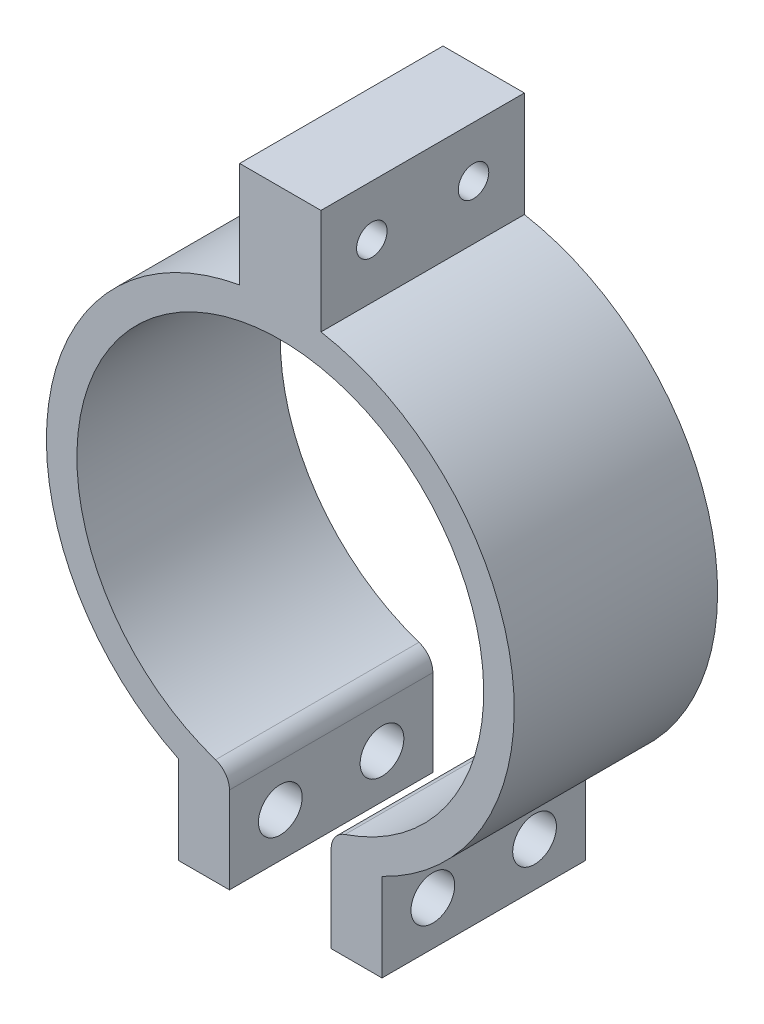
SolidWorks part; units mm, degrees
ref_plane "前视基准面" through (0, 0, 0) normal (0, 0, 1) x (1, 0, 0)
ref_plane "上视基准面" through (0, 0, 0) normal (0, 1, 0) x (1, 0, 0)
ref_plane "右视基准面" through (0, 0, 0) normal (1, 0, 0) x (0, 0, -1)
sketch "草图1" plane through (0, 0, 0) normal (0, 0, 1) x (1, 0, 0)
  circle A0 centre (0, 0) radius 20
  circle A1 centre (0, 0) radius 23
  dimension "D1" = 40
  dimension "D2" = 46
extrude "凸台-拉伸1" add sketch "草图1" along normal blind 20
sketch "草图2" plane through (0, 0, 20) normal (0, 0, 1) x (1, 0, 0)
  line L1 (5, -10.1845) -> (-5, -10.1845)
  line L2 (5, -10.1845) -> (5, -29.8155)
  line L3 (5, -29.8155) -> (-5, -29.8155)
  line L4 (-5, -10.1845) -> (-5, -29.8155)
  line L5 (5, -10.1845) -> (-5, -29.8155) construction
  line L6 (5, -29.8155) -> (-5, -10.1845) construction
  circle A0 centre (0, 0) radius 20 construction
  point P0 (0, -20)
  dimension "D1" = 10
extrude "切除-拉伸1" cut sketch "草图2" against normal blind 20
sketch "草图3" plane through (0, 0, 20) normal (0, 0, 1) x (1, 0, 0)
  line L1 (-5, -19.3649) -> (-10, -19.3649)
  line L2 (-5, -19.3649) -> (-5, -29.3649)
  line L3 (-5, -29.3649) -> (-10, -29.3649)
  line L4 (-10, -19.3649) -> (-10, -29.3649)
  line L5 (5, -19.3649) -> (10, -19.3649)
  line L6 (5, -19.3649) -> (5, -29.3649)
  line L7 (5, -29.3649) -> (10, -29.3649)
  line L8 (10, -19.3649) -> (10, -29.3649)
  dimension "D1" = 5
  dimension "D2" = 5
  dimension "D3" = 10
  dimension "D4" = 10
extrude "凸台-拉伸2" add sketch "草图3" against normal blind 20
fillet "圆角1" radius 2 2 edges at (-5, -19.3649, 10) (5, -19.3649, 10)
sketch "草图4" plane through (10, 0, 0) normal (1, 0, 0) x (0, 0, -1)
  line L0 (-20, -29.3649) -> (-20, -20.7123) construction
  line L1 (0, -29.3649) -> (0, -20.7123) construction
  line L2 (0, -29.3649) -> (-20, -29.3649) construction
  circle A0 centre (-15, -25.0386) radius 2.15
  circle A1 centre (-5, -25.0386) radius 2.15
  dimension "D1" = 4.3
  dimension "D2" = 4.3
  dimension "D3" = 5
  dimension "D4" = 5
  dimension "D5" = 4.3263
  dimension "D6" = 4.3263
extrude "切除-拉伸2" cut sketch "草图4" against normal blind 20
sketch "草图5" plane through (0, 0, 0) normal (0, 0, -1) x (-1, 0, 0)
  line L1 (4, 33) -> (-4, 33)
  line L2 (4, 33) -> (4, 22)
  line L3 (4, 22) -> (-4, 22)
  line L4 (-4, 33) -> (-4, 22)
  line L5 (4, 33) -> (-4, 22) construction
  line L6 (4, 22) -> (-4, 33) construction
  point P0 (0, 27.5)
  point P5 (0, 33)
  dimension "D1" = 11
  dimension "D2" = 8
  dimension "D3" = 22
extrude "凸台-拉伸3" add sketch "草图5" against normal blind 20
sketch "草图6" plane through (4, 0, 0) normal (1, 0, 0) x (0, 0, -1)
  line L0 (-20, 33) -> (-20, 22.6495) construction
  line L1 (0, 33) -> (0, 22.6495) construction
  line L2 (-20, 33) -> (0, 33) construction
  circle A0 centre (-5, 28) radius 1.5
  circle A1 centre (-15, 28) radius 1.5
  dimension "D1" = 3
  dimension "D2" = 3
  dimension "D3" = 5
  dimension "D4" = 5
  dimension "D5" = 5
  dimension "D6" = 5
extrude "切除-拉伸3" cut sketch "草图6" against normal blind 23
